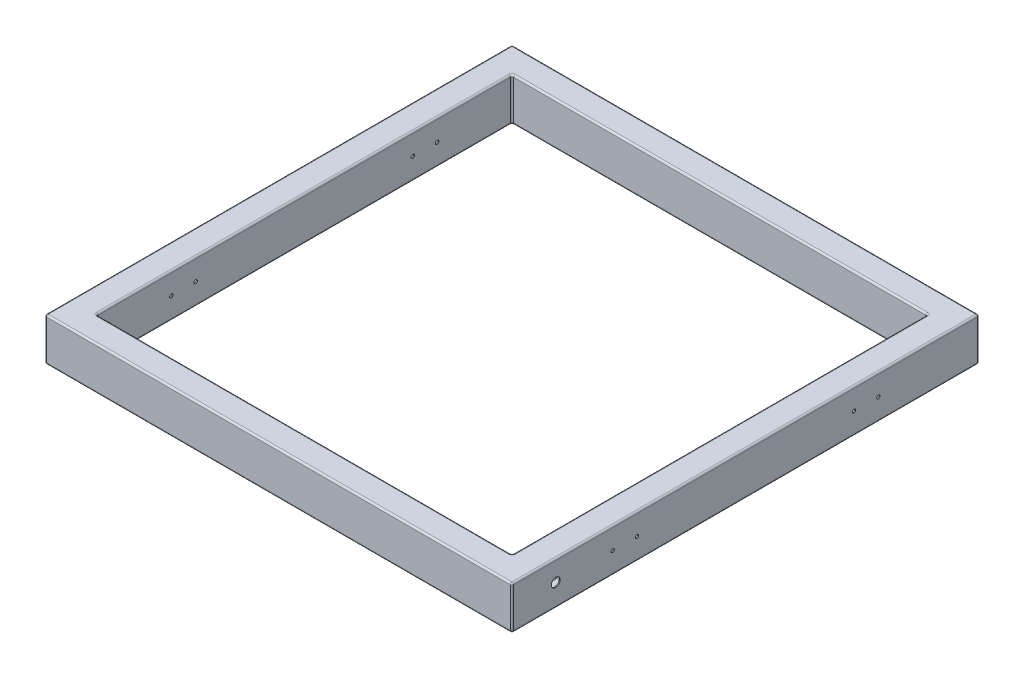
SolidWorks part; units mm, degrees
material "Plain Carbon Steel"
ref_plane "Front" through (0, 0, 0) normal (0, 0, 1) x (1, 0, 0)
ref_plane "Top" through (0, 0, 0) normal (0, 1, 0) x (1, 0, 0)
ref_plane "Right" through (0, 0, 0) normal (1, 0, 0) x (0, 0, -1)
sketch "Sketch1" plane through (0, 0, 0) normal (0, 1, 0) x (1, 0, 0)
  line L1 (-680, 680) -> (680, 680)
  line L2 (-680, 680) -> (-680, -680)
  line L3 (-680, -680) -> (680, -680)
  line L4 (680, 680) -> (680, -680)
  line L5 (-680, 680) -> (680, -680) construction
  line L6 (-680, -680) -> (680, 680) construction
  line L7 (-605, 605) -> (605, 605)
  line L8 (-605, 605) -> (-605, -605)
  line L9 (-605, -605) -> (605, -605)
  line L10 (605, 605) -> (605, -605)
  line L11 (-605, 605) -> (605, -605) construction
  line L12 (-605, -605) -> (605, 605) construction
  point P0 (0, 0)
  point P6 (0, 0)
  dimension "D1" = 1210
  dimension "D2" = 75
extrude "Boss-Extrude1" add sketch "Sketch1" along normal blind 125
fillet "Fillet1" radius 5 24 edges at (-680, 62.5, 680) (680, 62.5, 680) (0, 0, 680) (0, 125, 680) (-680, 125, 0) (0, 125, -680) (680, 125, 0) (-605, 125, 0) (0, 125, 605) (605, 125, 0) (0, 125, -605) (680, 62.5, -680) (-680, 62.5, -680) (-680, 0, 0) (0, 0, -680) (680, 0, 0) (605, 62.5, -605) (-605, 62.5, -605) (-605, 62.5, 605) (605, 62.5, 605) (0, 0, 605) (-605, 0, 0) (0, 0, -605) (605, 0, 0)
shell "Shell1" thickness 3
sketch "Sketch2" plane through (-680, 0, 0) normal (-1, 0, 0) x (0, 0, 1)
  circle A0 centre (-387, 62.5) radius 5
  circle A1 centre (-316, 62.5) radius 5
  circle A2 centre (387, 62.5) radius 5
  circle A3 centre (316, 62.5) radius 5
  dimension "D1" = 10
extrude "Cut-Extrude1" cut sketch "Sketch2" against normal through all
sketch "Sketch3" plane through (680, 0, 0) normal (1, 0, 0) x (0, 0, -1)
  line L0 (-500, 65) -> (-605, 65) construction
  line L1 (-500, -415) -> (-500, 1224) construction
  line L2 (-605, -353.25) -> (-605, -226.75) construction
  line L3 (-675, 125) -> (675, 125) construction
  circle A0 centre (-552.5, 65) radius 13
  dimension "D2" = 26
  dimension "D1" = 60
extrude "Cut-Extrude2" cut sketch "Sketch3" against normal up to surface (75 mm away) up to face at (605, 62.5, -382)
